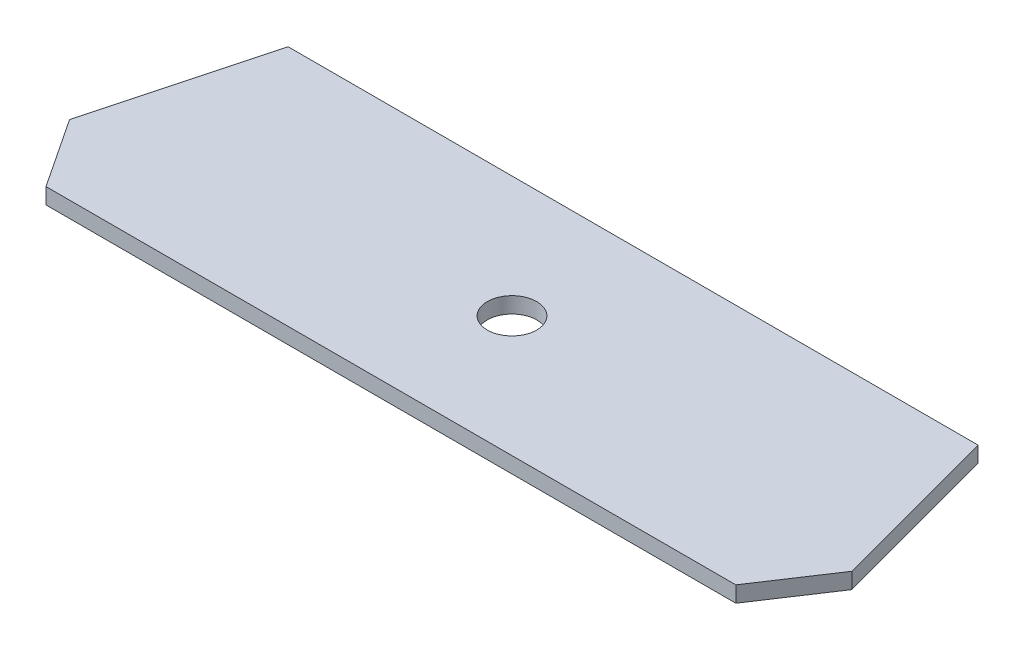
SolidWorks part; units mm, degrees
ref_plane "Front Plane" through (0, 0, 0) normal (0, 0, 1) x (1, 0, 0)
ref_plane "Top Plane" through (0, 0, 0) normal (0, 1, 0) x (1, 0, 0)
ref_plane "Right Plane" through (0, 0, 0) normal (1, 0, 0) x (0, 0, -1)
sketch "Sketch1" plane through (0, 0, 0) normal (0, 1, 0) x (1, 0, 0)
  line L0 (-54.991, 19.304) -> (-62.357, -8.1863)
  line L1 (-54.991, -19.304) -> (54.991, -19.304)
  line L2 (-54.991, -19.304) -> (-54.991, 19.304) construction
  line L3 (-54.991, 19.304) -> (54.991, 19.304)
  line L4 (54.991, -19.304) -> (54.991, 19.304) construction
  line L5 (-54.991, -19.304) -> (54.991, 19.304) construction
  line L6 (-54.991, 19.304) -> (54.991, -19.304) construction
  line L7 (-62.357, -8.1863) -> (-54.991, -19.304)
  line L8 (54.991, -19.304) -> (62.357, -8.1863)
  line L9 (62.357, -8.1863) -> (54.991, 19.304)
  point P0 (0, 0)
  dimension "D1" = 38.608
  dimension "D2" = 109.982
  dimension "D3" = 124.714
  dimension "D4" = 15
  dimension "D5" = 15
extrude "Boss-Extrude1" add sketch "Sketch1" along normal blind 2.54
sketch "Sketch2" plane through (0, 2.54, 0) normal (0, 1, 0) x (1, 0, 0)
  circle A0 centre (0, 0) radius 3.937
  dimension "D1" = 7.874
extrude "Cut-Extrude4" cut sketch "Sketch2" against normal up to surface (2.54 mm away) up to face at (0, 0, 2.7288)
